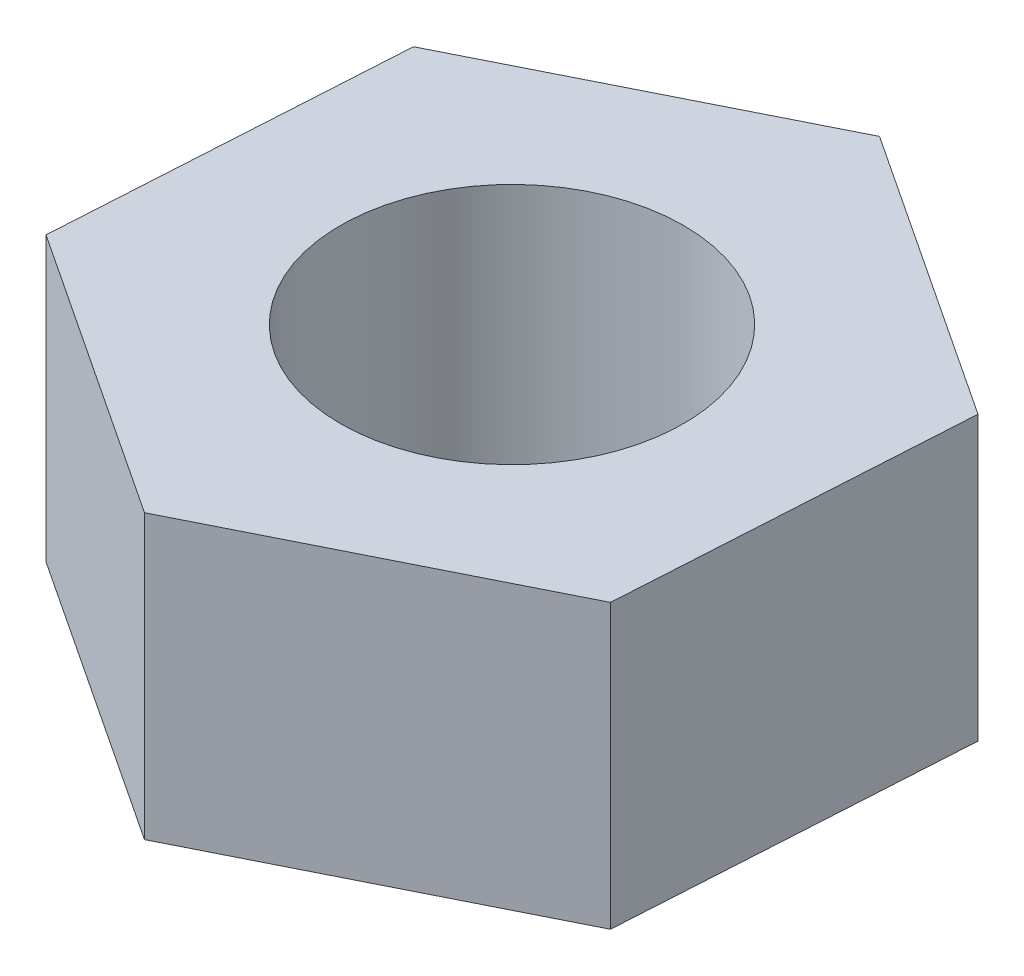
SolidWorks part; units mm, degrees
material "AISI 316 Annealed Stainless Steel Bar (SS)"
ref_plane "Front Plane" through (0, 0, 0) normal (0, 0, 1) x (1, 0, 0)
ref_plane "Top Plane" through (0, 0, 0) normal (0, 1, 0) x (1, 0, 0)
ref_plane "Right Plane" through (0, 0, 0) normal (1, 0, 0) x (0, 0, -1)
sketch "Sketch1" plane through (0, 0, 0) normal (0, 1, 0) x (1, 0, 0)
  line L1 (-8.7788, -4.3894) -> (-0.5881, -9.7973)
  line L2 (-0.5881, -9.7973) -> (8.1907, -5.4079)
  line L3 (8.1907, -5.4079) -> (8.7788, 4.3894)
  line L4 (8.7788, 4.3894) -> (0.5881, 9.7973)
  line L5 (0.5881, 9.7973) -> (-8.1907, 5.4079)
  line L6 (-8.1907, 5.4079) -> (-8.7788, -4.3894)
  circle A1 centre (0, 0) radius 4.85
  dimension "D2" = 9.7
extrude "Boss-Extrude1" add sketch "Sketch1" along normal blind 8
